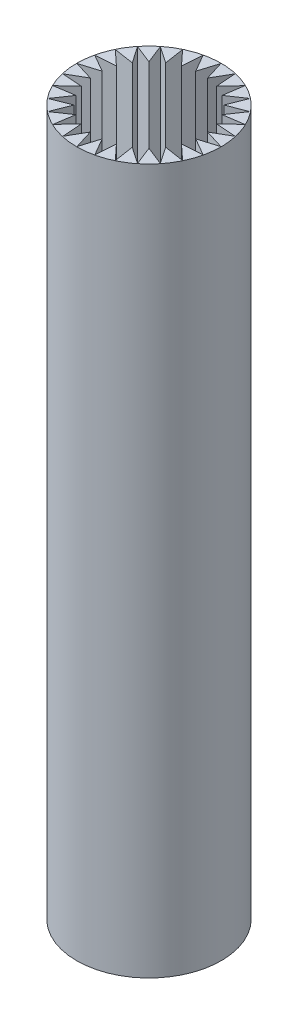
SolidWorks part; units mm, degrees
ref_plane "Front Plane" through (0, 0, 0) normal (0, 0, 1) x (1, 0, 0)
ref_plane "Top Plane" through (0, 0, 0) normal (0, 1, 0) x (1, 0, 0)
ref_plane "Right Plane" through (0, 0, 0) normal (1, 0, 0) x (0, 0, -1)
sketch "Sketch1" plane through (0, 0, 0) normal (0, 1, 0) x (1, 0, 0)
  line L0 (-1.8555, -1.6783) -> (1.8555, -1.6783)
  circle A0 centre (0, 0) radius 3.175
  arc A1 (1.8555, -1.6783) -> (-1.8555, -1.6783) centre (0, 0) ccw
  dimension "D1" = 6.35
  dimension "D2" = 5.0038
  dimension "D3" = 3.711
extrude "Boss-Extrude1" add sketch "Sketch1" along normal blind 18
sketch "Sketch2" plane through (0, 18, 0) normal (0, 1, 0) x (1, 0, 0)
  circle A0 centre (0, 0) radius 3.175
extrude "Boss-Extrude2" add sketch "Sketch2" along normal blind 0.254
sketch "Sketch4" plane through (0, 18.254, 0) normal (0, 1, 0) x (1, 0, 0)
  circle A0 centre (0, 0) radius 3.175
  dimension "D1" = 6.35
extrude "Boss-Extrude3" add sketch "Sketch4" along normal blind 12.7
sketch "Sketch5" plane through (0, 30.954, 0) normal (0, 1, 0) x (1, 0, 0)
  line L0 (0, 0) -> (0, 3.175) construction
  line L3 (0.2607, 2.3141) -> (0.7112, 3.0943)
  line L4 (-0.2607, 2.3141) -> (-0.7112, 3.0943)
  line L5 (0.2607, 2.3141) -> (-0.0048, 3.175)
  line L6 (0.7691, 2.1981) -> (1.3819, 2.8585)
  line L7 (0.7691, 2.1981) -> (0.7018, 3.0965)
  line L8 (1.239, 1.9718) -> (1.9833, 2.4793)
  line L9 (1.239, 1.9718) -> (1.3732, 2.8627)
  line L10 (1.6467, 1.6467) -> (2.4853, 1.9758)
  line L11 (1.6467, 1.6467) -> (1.9758, 2.4853)
  line L12 (1.9718, 1.239) -> (2.8627, 1.3732)
  line L13 (1.9718, 1.239) -> (2.4793, 1.9833)
  line L14 (2.1981, 0.7691) -> (3.0965, 0.7018)
  line L15 (2.1981, 0.7691) -> (2.8585, 1.3819)
  line L16 (2.3141, 0.2607) -> (3.175, -0.0048)
  line L17 (2.3141, 0.2607) -> (3.0943, 0.7112)
  line L18 (2.3141, -0.2607) -> (3.0943, -0.7112)
  line L19 (2.3141, -0.2607) -> (3.175, 0.0048)
  line L20 (2.1981, -0.7691) -> (2.8585, -1.3819)
  line L21 (2.1981, -0.7691) -> (3.0965, -0.7018)
  line L22 (1.9718, -1.239) -> (2.4793, -1.9833)
  line L23 (1.9718, -1.239) -> (2.8627, -1.3732)
  line L24 (1.6467, -1.6467) -> (1.9758, -2.4853)
  line L25 (1.6467, -1.6467) -> (2.4853, -1.9758)
  line L26 (1.239, -1.9718) -> (1.3732, -2.8627)
  line L27 (1.239, -1.9718) -> (1.9833, -2.4793)
  line L28 (0.7691, -2.1981) -> (0.7018, -3.0965)
  line L29 (0.7691, -2.1981) -> (1.3819, -2.8585)
  line L30 (0.2607, -2.3141) -> (-0.0048, -3.175)
  line L31 (0.2607, -2.3141) -> (0.7112, -3.0943)
  line L32 (-0.2607, -2.3141) -> (-0.7112, -3.0943)
  line L33 (-0.2607, -2.3141) -> (0.0048, -3.175)
  line L34 (-0.7691, -2.1981) -> (-1.3819, -2.8585)
  line L35 (-0.7691, -2.1981) -> (-0.7018, -3.0965)
  line L36 (-1.239, -1.9718) -> (-1.9833, -2.4793)
  line L37 (-1.239, -1.9718) -> (-1.3732, -2.8627)
  line L38 (-1.6467, -1.6467) -> (-2.4853, -1.9758)
  line L39 (-1.6467, -1.6467) -> (-1.9758, -2.4853)
  line L40 (-1.9718, -1.239) -> (-2.8627, -1.3732)
  line L41 (-1.9718, -1.239) -> (-2.4793, -1.9833)
  line L42 (-2.1981, -0.7691) -> (-3.0965, -0.7018)
  line L43 (-2.1981, -0.7691) -> (-2.8585, -1.3819)
  line L44 (-2.3141, -0.2607) -> (-3.175, 0.0048)
  line L45 (-2.3141, -0.2607) -> (-3.0943, -0.7112)
  line L46 (-2.3141, 0.2607) -> (-3.0943, 0.7112)
  line L47 (-2.3141, 0.2607) -> (-3.175, -0.0048)
  line L48 (-2.1981, 0.7691) -> (-2.8585, 1.3819)
  line L49 (-2.1981, 0.7691) -> (-3.0965, 0.7018)
  line L50 (-1.9718, 1.239) -> (-2.4793, 1.9833)
  line L51 (-1.9718, 1.239) -> (-2.8627, 1.3732)
  line L52 (-1.6467, 1.6467) -> (-1.9758, 2.4853)
  line L53 (-1.6467, 1.6467) -> (-2.4853, 1.9758)
  line L54 (-1.239, 1.9718) -> (-1.3732, 2.8627)
  line L55 (-1.239, 1.9718) -> (-1.9833, 2.4793)
  line L56 (-0.7691, 2.1981) -> (-0.7018, 3.0965)
  line L57 (-0.7691, 2.1981) -> (-1.3819, 2.8585)
  line L58 (-0.2607, 2.3141) -> (0.0048, 3.175)
  arc A1 (-1.3732, 2.8627) -> (-1.3819, 2.8585) centre (0, 0) ccw
  arc A2 (-2.4793, 1.9833) -> (-2.4853, 1.9758) centre (0, 0) ccw
  arc A3 (-3.0943, 0.7112) -> (-3.0965, 0.7018) centre (0, 0) ccw
  arc A4 (-3.0965, -0.7018) -> (-3.0943, -0.7112) centre (0, 0) ccw
  arc A5 (-1.9833, -2.4793) -> (-1.9758, -2.4853) centre (0, 0) ccw
  arc A6 (-0.7112, -3.0943) -> (-0.7018, -3.0965) centre (0, 0) ccw
  arc A7 (1.3732, -2.8627) -> (1.3819, -2.8585) centre (0, 0) ccw
  arc A8 (2.4793, -1.9833) -> (2.4853, -1.9758) centre (0, 0) ccw
  arc A9 (3.0943, -0.7112) -> (3.0965, -0.7018) centre (0, 0) ccw
  arc A10 (3.0965, 0.7018) -> (3.0943, 0.7112) centre (0, 0) ccw
  arc A11 (2.4853, 1.9758) -> (2.4793, 1.9833) centre (0, 0) ccw
  arc A12 (1.3819, 2.8585) -> (1.3732, 2.8627) centre (0, 0) ccw
  circle A15 centre (0, 0) radius 3.175
  circle A16 centre (0, 0) radius 3.175
  circle A17 centre (0, 0) radius 3.175
  circle A18 centre (0, 0) radius 3.175
  circle A19 centre (0, 0) radius 3.175
  circle A20 centre (0, 0) radius 3.175
  circle A21 centre (0, 0) radius 3.175
  circle A22 centre (0, 0) radius 3.175
  circle A23 centre (0, 0) radius 3.175
  circle A24 centre (0, 0) radius 3.175
  circle A25 centre (0, 0) radius 3.175
  circle A26 centre (0, 0) radius 3.175
  circle A27 centre (0, 0) radius 3.175
  circle A28 centre (0, 0) radius 3.175
  arc A29 (-1.9758, 2.4853) -> (-0.7112, 3.0943) centre (0, 0) ccw
  arc A30 (-2.8585, 1.3819) -> (-1.9833, 2.4793) centre (0, 0) ccw
  arc A31 (-2.8585, 1.3819) -> (-2.8627, 1.3732) centre (0, 0) ccw
  arc A32 (-2.4793, 1.9833) -> (-2.4853, 1.9758) centre (0, 0) ccw
  arc A33 (-3.175, 0.0048) -> (-1.9833, 2.4793) centre (0, 0) ccw
  arc A34 (-2.8627, -1.3732) -> (-3.175, -0.0048) centre (0, 0) ccw
  arc A35 (-1.3819, -2.8585) -> (-2.4793, -1.9833) centre (0, 0) ccw
  arc A36 (-0.0048, -3.175) -> (-1.3732, -2.8627) centre (0, 0) ccw
  arc A37 (1.9758, -2.4853) -> (0.7112, -3.0943) centre (0, 0) ccw
  arc A38 (2.8585, -1.3819) -> (1.9833, -2.4793) centre (0, 0) ccw
  arc A39 (3.175, -0.0048) -> (2.8627, -1.3732) centre (0, 0) ccw
  arc A40 (2.8627, 1.3732) -> (3.175, 0.0048) centre (0, 0) ccw
  arc A41 (1.9833, 2.4793) -> (2.8585, 1.3819) centre (0, 0) ccw
  arc A42 (0.7112, 3.0943) -> (1.9758, 2.4853) centre (0, 0) ccw
  arc A43 (0.0048, 3.175) -> (0.7018, 3.0965) centre (0, 0) ccw [skipped]
  circle A44 centre (0, 0) radius 3.175 [skipped]
  point P117 (0, 0)
  dimension "D1" = 6.35
  dimension "D3" = 30
  dimension "D4" = 28
extrude "Cut-Extrude3" cut sketch "Sketch5" against normal blind 12.7 contours L58 L4 L56 L57 L54 L55 L52 L53 L50 L51 L48 L49 L46 L47 L44 L45 L42 L43 L40 L41 L38 L39 L36 L37 L34 L35 L32 L33 L30 L31 L28 L29 L26 L27 L24 L25 L22 L23 L20 L21 L18 L19 L16 L17 L14 L15 L12 L13 L10 L11 L8
